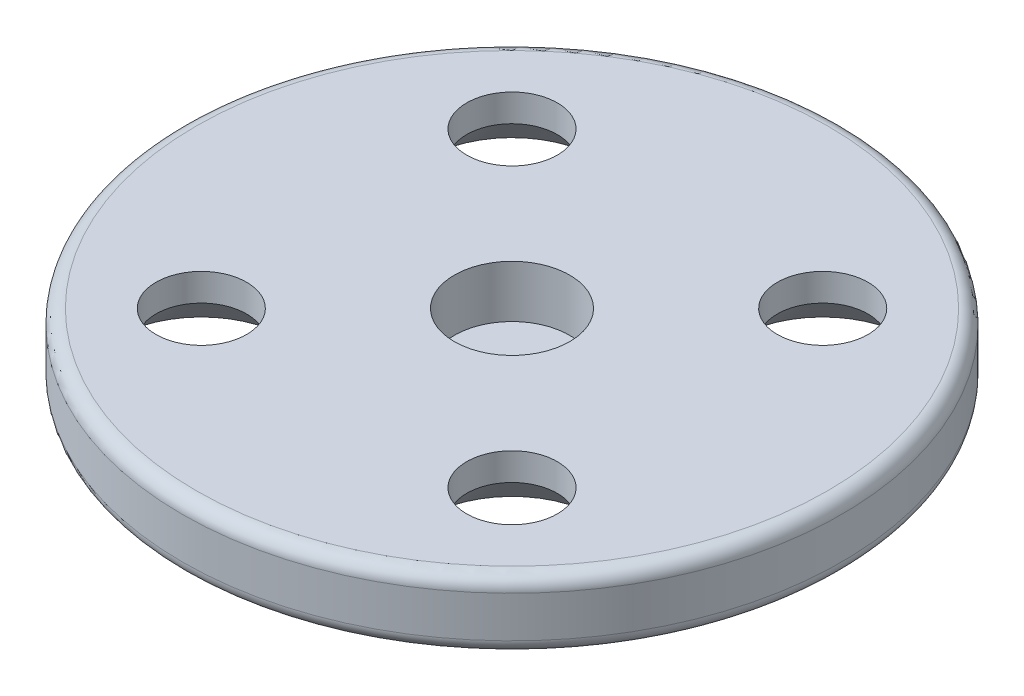
SolidWorks part; units mm, degrees
ref_plane "Front Plane" through (0, 0, 0) normal (0, 0, 1) x (1, 0, 0)
ref_plane "Top Plane" through (0, 0, 0) normal (0, 1, 0) x (1, 0, 0)
ref_plane "Right Plane" through (0, 0, 0) normal (1, 0, 0) x (0, 0, -1)
sketch "Sketch1" plane through (0, 0, 0) normal (0, 1, 0) x (1, 0, 0)
  line L1 (-5.6569, -5.6569) -> (5.6569, -5.6569) construction
  line L2 (-5.6569, -5.6569) -> (-5.6569, 5.6569) construction
  line L3 (-5.6569, 5.6569) -> (5.6569, 5.6569) construction
  line L4 (5.6569, -5.6569) -> (5.6569, 5.6569) construction
  line L5 (-5.6569, -5.6569) -> (5.6569, 5.6569) construction
  line L6 (-5.6569, 5.6569) -> (5.6569, -5.6569) construction
  circle A0 centre (0, 0) radius 12
  circle A1 centre (-5.6569, 5.6569) radius 1.65
  circle A2 centre (5.6569, 5.6569) radius 1.65
  circle A3 centre (5.6569, -5.6569) radius 1.65
  circle A4 centre (-5.6569, -5.6569) radius 1.65
  dimension "D1" = 24
  dimension "D3" = 3.3
  dimension "D2" = 16
extrude "Boss-Extrude1" add sketch "Sketch1" along normal blind 2.5
sketch "Sketch2" plane through (0, 2.5, 0) normal (0, 1, 0) x (1, 0, 0)
  circle A0 centre (0, 0) radius 2.1
  dimension "D1" = 4.2
extrude "Cut-Extrude1" cut sketch "Sketch2" against normal blind 1.9
chamfer "Chamfer1" distance 1.5 angle 45 4 edges at (5.6569, 0, -4.0069) (5.6569, 0, 7.3069) (-5.6569, 0, -4.0069) (-5.6569, 0, 7.3069)
fillet "Fillet1" radius 0.5 2 edges at (0, 0, 12) (0, 2.5, 12)
